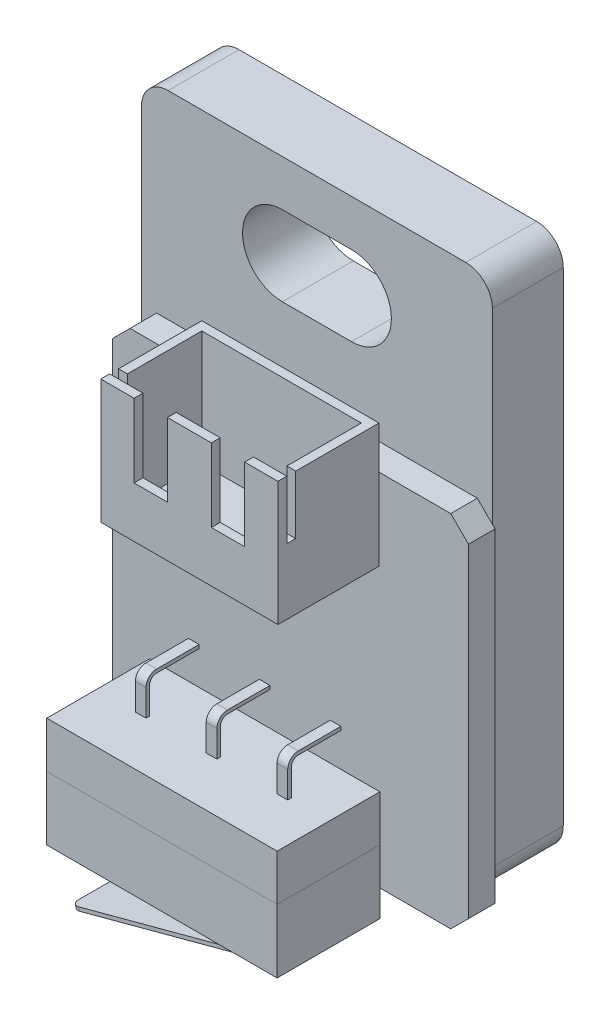
SolidWorks part; units mm, degrees
ref_plane "Front Plane" through (0, 0, 0) normal (0, 0, 1) x (1, 0, 0)
ref_plane "Top Plane" through (0, 0, 0) normal (0, 1, 0) x (1, 0, 0)
ref_plane "Right Plane" through (0, 0, 0) normal (1, 0, 0) x (0, 0, -1)
sketch "Sketch1" plane through (0, 0, 0) normal (0, 0, 1) x (1, 0, 0)
  line L1 (-9.9, 15.15) -> (9.9, 15.15)
  line L2 (-9.9, 15.15) -> (-9.9, -15.15)
  line L3 (-9.9, -15.15) -> (9.9, -15.15)
  line L4 (9.9, 15.15) -> (9.9, -15.15)
  line L5 (-9.9, 15.15) -> (9.9, -15.15) construction
  line L6 (-9.9, -15.15) -> (9.9, 15.15) construction
  point P0 (0, 0)
  dimension "D1" = 19.8
  dimension "D2" = 30.3
extrude "Boss-Extrude1" add sketch "Sketch1" along normal blind 4
fillet "Fillet1" radius 1.5 4 edges at (9.9, -15.15, 2) (-9.9, -15.15, 2) (-9.9, 15.15, 2) (9.9, 15.15, 2)
sketch "Sketch2" plane through (0, 0, 4) normal (0, 0, 1) x (1, 0, 0)
  line L0 (0, 15.15) -> (0, 0) construction
  line L1 (8.4, 15.15) -> (-8.4, 15.15) construction
  line L2 (-1.95, 10.3) -> (1.95, 10.3) construction
  line L3 (-1.95, 12.55) -> (1.95, 12.55)
  line L4 (-1.95, 8.05) -> (1.95, 8.05)
  arc A0 (-1.95, 12.55) -> (-1.95, 8.05) centre (-1.95, 10.3) ccw
  arc A1 (1.95, 8.05) -> (1.95, 12.55) centre (1.95, 10.3) ccw
  point P7 (0, 10.3)
  dimension "D2" = 8.4
  dimension "D1" = 4.5
  dimension "D3" = 2.6
extrude "Cut-Extrude1" cut sketch "Sketch2" against normal through all
sketch "Sketch3" plane through (0, 0, 4) normal (0, 0, 1) x (1, 0, 0)
  line L0 (0, 0) -> (0, -6.2) construction
  line L1 (-8.4, -15.15) -> (8.4, -15.15) construction
  line L2 (-10.05, 3.95) -> (10.05, 3.95)
  line L3 (-10.05, 3.95) -> (-10.05, -16.35)
  line L4 (-10.05, -16.35) -> (10.05, -16.35)
  line L5 (10.05, 3.95) -> (10.05, -16.35)
  line L6 (-10.05, 3.95) -> (10.05, -16.35) construction
  line L7 (-10.05, -16.35) -> (10.05, 3.95) construction
  dimension "D1" = 20.1
  dimension "D2" = 1.2
  dimension "D3" = 20.3
extrude "Boss-Extrude2" add sketch "Sketch3" along normal blind 1.5 separate body
sketch "Sketch4" plane through (0, 0, 5.5) normal (0, 0, 1) x (1, 0, 0)
  line L0 (-10.05, -16.35) -> (10.05, -16.35) construction
  line L1 (-7.95, -11.65) -> (5.05, -11.65)
  line L2 (-7.95, -11.65) -> (-7.95, -17.85)
  line L3 (-7.95, -17.85) -> (5.05, -17.85)
  line L4 (5.05, -11.65) -> (5.05, -17.85)
  line L5 (-10.05, 3.95) -> (-10.05, -16.35) construction
  dimension "D1" = 1.5
  dimension "D2" = 2.1
  dimension "D3" = 6.2
  dimension "D4" = 13
extrude "Boss-Extrude3" add sketch "Sketch4" along normal blind 5.8 separate body
sketch "Sketch5" plane through (0, 0, 5.5) normal (0, 0, 1) x (1, 0, 0)
  line L0 (0, 0) -> (0, 2.85) construction
  line L1 (10.05, 3.95) -> (-10.05, 3.95) construction
  line L2 (-5, -0.65) -> (5, -0.65)
  line L3 (-5, -0.65) -> (-5, 6.35)
  line L4 (-5, 6.35) -> (5, 6.35)
  line L5 (5, -0.65) -> (5, 6.35)
  line L6 (-5, -0.65) -> (5, 6.35) construction
  line L7 (-5, 6.35) -> (5, -0.65) construction
  dimension "D1" = 7
  dimension "D2" = 10
  dimension "D3" = 2.4
extrude "Boss-Extrude4" add sketch "Sketch5" along normal blind 5.7 separate body
shell "Shell1" thickness 0.5
sketch "Sketch6" plane through (0, 0, 11.2) normal (0, 0, 1) x (1, 0, 0)
  line L0 (5, 6.35) -> (-5, 6.35) construction
  line L1 (1.2398, 6.35) -> (3.1201, 6.35)
  line L2 (1.2398, 6.35) -> (1.2398, 2.2128)
  line L3 (1.2398, 2.2128) -> (3.1201, 2.2128)
  line L4 (3.1201, 6.35) -> (3.1201, 2.2128)
  line L5 (0, 6.35) -> (0, -0.65) construction
  line L6 (-5, -0.65) -> (5, -0.65) construction
  line L7 (-1.2398, 2.2128) -> (-3.1201, 2.2128)
  line L8 (-3.1201, 6.35) -> (-3.1201, 2.2128)
  line L9 (-1.2398, 6.35) -> (-3.1201, 6.35)
  line L10 (-1.2398, 6.35) -> (-1.2398, 2.2128)
extrude "Cut-Extrude2" cut sketch "Sketch6" against normal up to next (0.5 mm away)
sketch "Sketch7" plane through (0, 0, 11.3) normal (0, 0, 1) x (1, 0, 0)
  line L0 (-7.95, -14.25) -> (5.05, -14.25)
  line L1 (-7.95, -11.65) -> (-7.95, -17.85) construction
  line L2 (5.05, -17.85) -> (5.05, -11.65) construction
  line L3 (-7.95, -17.85) -> (5.05, -17.85) construction
  dimension "D1" = 3.6
split "Split1" trim tools "Sketch7" bodies to split 104 resulting bodies 107 108
ref_plane "Plane1" through (0, 0, 8.4) normal (0, 0, -1) x (-1, 0, 0)
sketch "Sketch8" plane through (0, 0, 8.4) normal (0, 0, -1) x (-1, 0, 0)
  line L0 (-3.8647, -18.0915) -> (7.7264, -21.1973)
  line L1 (7.95, -17.85) -> (-5.05, -17.85) construction
  line L2 (-5.05, -17.85) -> (-5.05, -14.25) construction
  arc A0 (-3.8647, -18.0915) -> (-4.05, -17.85) centre (-3.8, -17.85) cw
  dimension "D1" = 0.25
  dimension "D2" = 15
  dimension "D3" = 1
  dimension "D4" = 12
extrude "Extrude-Thin1" add sketch "Sketch8" along normal mid plane 3.6 separate body thin
fillet "Fillet2" radius 0.5 2 edges at (-7.7005, -21.2939, 6.6) (-7.7005, -21.2939, 10.2)
sketch "Sketch10" plane through (4.8335, -18.0389, 0) normal (0.2588, -0.9659, 0) x (0.9659, 0.2588, 0)
  line L0 (-12.9494, 8.4) -> (-0.9494, 8.4) construction
  line L1 (-12.9494, 7.1) -> (-12.9494, 9.7) construction
  line L2 (-0.9494, 6.6) -> (-0.9494, 10.2) construction
  line L3 (-8.5276, 8.7748) -> (-0.5147, 9.05)
  line L8 (-0.5147, 6.6) -> (-0.5147, 10.2) construction
  line L9 (-8.5276, 8.0252) -> (-0.5147, 7.75)
  line L10 (-0.5147, 9.05) -> (-0.5147, 7.75)
  circle A0 centre (-8.5147, 8.4) radius 0.375
  line M10 (-0.9494, 6.6) -> (-0.9494, 10.2)
  dimension "D3" = 0.75
  dimension "D1" = 1.3
  dimension "D2" = 8
extrude "Cut-Extrude3" cut sketch "Sketch10" against normal through all contours L0 A0 L9 M10 | L10 L3 L9 M10 | A0 L0 L3 M10 | A0 L0 | L0 A0
sketch "Sketch11" plane through (0, -17.85, 0) normal (0, -1, 0) x (1, 0, 0)
  line L0 (5.05, 8.4) -> (1.8, 8.4) construction
  line L1 (5.05, 11.3) -> (5.05, 5.5) construction
  line L2 (-7.1917, 6.6) -> (3.9165, 6.6) construction
  line L3 (1.05, 10.2) -> (2.55, 10.2)
  line L4 (1.05, 10.2) -> (1.05, 6.6)
  line L5 (1.05, 6.6) -> (2.55, 6.6)
  line L6 (2.55, 10.2) -> (2.55, 6.6)
  line L7 (1.05, 10.2) -> (2.55, 6.6) construction
  line L8 (1.05, 6.6) -> (2.55, 10.2) construction
  dimension "D1" = 1.5
  dimension "D2" = 2.5
extrude "Boss-Extrude5" add sketch "Sketch11" along normal blind 0.6 separate body
ref_plane "Plane2" through (-1.45, 0, 0) normal (1, 0, 0) x (0, 0, -1)
sketch "Sketch12" plane through (-1.45, 0, 0) normal (1, 0, 0) x (0, 0, -1)
  line L0 (-8.4, -11.65) -> (-8.4, -10.15)
  line L1 (-11.3, -11.65) -> (-5.5, -11.65) construction
  line L2 (-7.9, -9.65) -> (-5.5, -9.65)
  line L3 (-5.5, -16.35) -> (-5.5, 3.95) construction
  arc A0 (-8.4, -10.15) -> (-7.9, -9.65) centre (-7.9, -10.15) cw
  point P10 (-8.4, -9.65)
  dimension "D2" = 0.5
  dimension "D1" = 2
extrude "Extrude-Thin2" add sketch "Sketch12" along normal mid plane 0.6 separate body thin thin type mid plane wall 0.2
pattern_linear "LPattern1" count 2 spacing 4 along (1, 0, 0) count 2 spacing 4 along (-1, 0, 0) of bodies 112
sketch "Sketch14" plane through (0, 0, 0) normal (1, 0, 0) x (0, 0, -1)
  line L0 (-8.5, -0.65) -> (-8.5, -0.9)
  line L1 (-11.2, -0.65) -> (-5.5, -0.65) construction
  line L2 (-8.25, -1.15) -> (-5.5, -1.15)
  line L3 (-5.5, -16.35) -> (-5.5, 3.95) construction
  arc A0 (-8.5, -0.9) -> (-8.25, -1.15) centre (-8.25, -0.9) ccw
  dimension "D3" = 0.25
  dimension "D1" = 3
  dimension "D2" = 0.5
extrude "Extrude-Thin3" add sketch "Sketch14" along normal mid plane 0.5 separate body thin thin type mid plane wall 0.2
pattern_linear "LPattern2" count 2 spacing 3 along (-1, 0, 0) count 2 spacing 3 along (1, 0, 0) of bodies 119
chamfer "Chamfer1" distance 1 angle 45 4 edges at (10.05, 3.95, 4.75) (-10.05, 3.95, 4.75) (-10.05, -16.35, 4.75) (10.05, -16.35, 4.75)
sketch "Sketch16" plane through (5, 0, 0) normal (1, 0, 0) x (0, 0, -1)
  line L0 (-10.7, 6.35) -> (-10.7, -0.15) construction
  line L1 (-10.7, 3.05) -> (-10.2, 3.05)
  line L2 (-10.7, 3.05) -> (-10.7, 6.35)
  line L3 (-10.7, 6.35) -> (-10.2, 6.35)
  line L4 (-10.2, 3.05) -> (-10.2, 6.35)
  line L5 (-10.7, 6.35) -> (-6, 6.35) construction
  dimension "D1" = 0.5
  dimension "D2" = 3.3
extrude "Cut-Extrude4" cut sketch "Sketch16" against normal through all
sketch "Sketch17" [suppressed] plane through (0, 0, 4) normal (0, 0, 1) x (1, 0, 0)
  line L0 (0, 18.5) -> (0, 7.9) construction
  line L1 (10.3, 18.5) -> (-10.3, 18.5) construction
  line L2 (0, 9.4) -> (0, 6.4) construction
  line L3 (2.1, 9.4) -> (2.1, 6.4)
  line L4 (-2.1, 9.4) -> (-2.1, 6.4)
  arc A0 (2.1, 9.4) -> (-2.1, 9.4) centre (0, 9.4) ccw
  arc A1 (-2.1, 6.4) -> (2.1, 6.4) centre (0, 6.4) ccw
  point P7 (0, 7.9)
  dimension "D2" = 7.2
  dimension "D3" = 7
  dimension "D1" = 4.2
extrude "Cut-Extrude5" [suppressed] cut sketch "Sketch17" against normal through all
